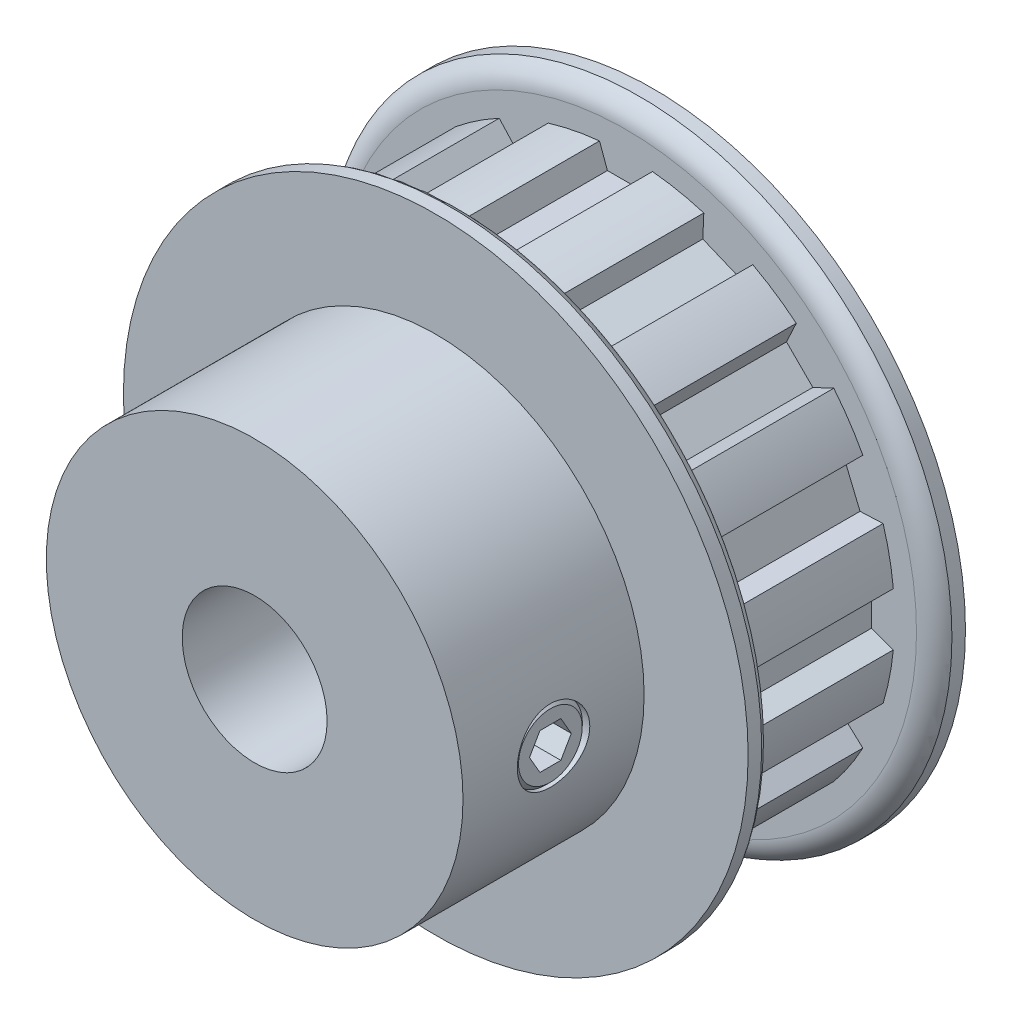
SolidWorks part; units mm, degrees
ref_plane "Front Plane" through (0, 0, 0) normal (0, 0, 1) x (1, 0, 0)
ref_plane "Top Plane" through (0, 0, 0) normal (0, 1, 0) x (1, 0, 0)
ref_plane "Right Plane" through (0, 0, 0) normal (1, 0, 0) x (0, 0, -1)
sketch "Sketch1" plane through (0, 0, 0) normal (0, 0, 1) x (1, 0, 0)
  line L0 (-2.3241, 23.4315) -> (-1.6307, 21.5265)
  line L1 (-1.6307, 21.5265) -> (1.6307, 21.5265)
  line L2 (1.6307, 21.5265) -> (2.3241, 23.4315)
  line L3 (-2.3241, 23.4315) -> (2.3241, 23.4315)
  line L4 (0, 0) -> (0, 21.5265) construction
  line L5 (0, 21.5265) -> (0, 25.0825) construction
  circle A0 centre (0, 0) radius 24.257 construction
  circle A1 centre (0, 0) radius 27.3812 construction
  circle A2 centre (0, 0) radius 23.5465 construction
  point P6 (0, 23.4315)
  point P11 (0, 24.257)
  point P13 (0, 27.3812)
  point P14 (0, 23.5465)
  dimension "D1" = 1.651
  dimension "D2" = 0.8255
sketch "Sketch2" plane through (0, 0, 0) normal (1, 0, 0) x (0, 0, -1)
  line L0 (-17.4625, 6.35) -> (17.4625, 6.35)
  line L1 (-17.4625, 6.35) -> (-17.4625, 18.2626)
  line L2 (-17.4625, 18.2626) -> (-1.5875, 18.2626)
  line L3 (-1.5875, 18.2626) -> (-1.5875, 27.3812)
  line L4 (-1.5875, 27.3812) -> (0.7874, 27.3812) construction
  line L5 (0.7874, 27.3812) -> (0.7874, 23.5465) construction
  line L6 (0.7874, 23.5465) -> (15.0876, 23.5465)
  line L7 (15.0876, 23.5465) -> (15.0876, 27.3812) construction
  line L8 (15.0876, 27.3812) -> (17.4625, 27.3812) construction
  line L9 (17.4625, 27.3812) -> (17.4625, 6.35)
  line L10 (-17.4625, 0) -> (17.4625, 0) construction
  line L13 (-1.5875, 27.3812) -> (-0.4001, 27.3812)
  line L14 (0.7874, 25.4638) -> (0.7874, 23.5465)
  line L15 (15.0876, 23.5465) -> (15.0876, 25.4638)
  line L16 (16.2751, 27.3812) -> (17.4625, 27.3812)
  arc A0 (0.7874, 25.4638) -> (-0.4001, 27.3812) centre (-1.3543, 25.4638) ccw
  arc A1 (15.0876, 25.4638) -> (16.2751, 27.3812) centre (17.2293, 25.4638) cw
  point P12 (0.7874, 25.4638)
  point P14 (-0.4001, 27.3812)
  point P20 (15.0876, 25.4638)
  point P21 (16.2751, 27.3812)
  point P25 (15.0876, 0)
  point P26 (0.7874, 0)
  dimension "Bore" = 12.7
  dimension "Hub Dia" = 36.5252
  dimension "Outside Width" = 19.05
  dimension "Inside Width" = 14.3002
revolve "Revolve1" add sketch "Sketch2" angle 360 mid plane about L10
sketch "Sketch3" plane through (0, 0, 0) normal (0, 0, 1) x (1, 0, 0)
  line L0 (-1.6307, 21.5265) -> (1.6307, 21.5265) construction
  line L1 (1.6307, 21.5265) -> (2.3241, 23.4315) construction
  line L2 (-2.3241, 23.4315) -> (-1.6307, 21.5265) construction
  line L3 (-1.6307, 21.5265) -> (1.6307, 21.5265)
  line L4 (1.6307, 21.5265) -> (2.3241, 23.4315)
  line L5 (-2.3241, 23.4315) -> (-1.6307, 21.5265)
  circle A0 centre (0, 0) radius 23.5465 construction
  arc A1 (2.3241, 23.4315) -> (-2.3241, 23.4315) centre (0, 0) ccw
extrude "Cut-Extrude1" cut sketch "Sketch3" against normal up to vertex (15.0876 mm away) from vertex at -0.7874 starting at point (0, 23.5465, -0.7874)
pattern_circular "CirPattern1" count 16 over 360 about axis through (0, 0, 0) along (0, 0, 1) of "Cut-Extrude1"
sketch "Sketch4" plane through (0, 0, 0) normal (1, 0, 0) x (0, -1, 0)
  line L0 (0, -1.5875) -> (0, -17.4625) construction
  line L1 (-18.2626, -1.5875) -> (18.2626, -1.5875) construction
  line L2 (-18.2626, -17.4625) -> (18.2626, -17.4625) construction
  circle A0 centre (0, -9.525) radius 3.175
  dimension "D1" = 6.35
extrude "Cut-Extrude2" cut sketch "Sketch4" along normal through all
ref_plane "Plane1" through (0, 0, 9.525) normal (0, 0, 1) x (1, 0, 0)
sketch "Sketch5" plane through (0, 0, 9.525) normal (0, 0, 1) x (1, 0, 0)
  line L0 (0, 0.1664) -> (0, 18.2626) construction
  line L1 (6.35, -2.794) -> (6.35, 0)
  line L2 (6.731, -3.175) -> (17.6035, -3.175)
  line L3 (6.35, 0) -> (18.2626, 0) construction
  line L4 (6.35, 0) -> (17.9845, 0)
  line L5 (17.9845, 0) -> (17.9845, -2.794)
  line L6 (6.731, -3.175) -> (6.35, -2.794)
  line L7 (17.9845, -2.794) -> (17.6035, -3.175)
  circle A0 centre (0, 0) radius 18.2626 construction
  circle A1 centre (0, 0) radius 6.35 construction
  point P2 (6.35, -3.175)
  point P11 (17.9845, -3.175)
revolve "Revolve2" add sketch "Sketch5" angle 360 mid plane about L4
sketch "Sketch6" plane through (17.9845, 5.3841, 0) normal (-1, 0, 0) x (0, -1, 0)
  line L1 (5.3841, 11.3581) -> (3.7966, 10.4415)
  line L2 (3.7966, 10.4415) -> (3.7966, 8.6085)
  line L3 (3.7966, 8.6085) -> (5.3841, 7.6919)
  line L4 (5.3841, 7.6919) -> (6.9716, 8.6085)
  line L5 (6.9716, 8.6085) -> (6.9716, 10.4415)
  line L6 (6.9716, 10.4415) -> (5.3841, 11.3581)
  circle A0 centre (5.3841, 9.525) radius 1.5875 construction
  dimension "D1" = 3.175
extrude "Cut-Extrude3" cut sketch "Sketch6" along normal blind 2.3813
equation "\"D2@Sketch1\" = \"D1@Sketch1\"/2"
equation "\"D1@Sketch4\" = \"Bore@Sketch2\"/2"
equation "\"D1@Sketch6\" = \"D1@Sketch4\"/2"
equation "\"D1@Cut-Extrude3\" = \"D1@Sketch6\"*.75"
